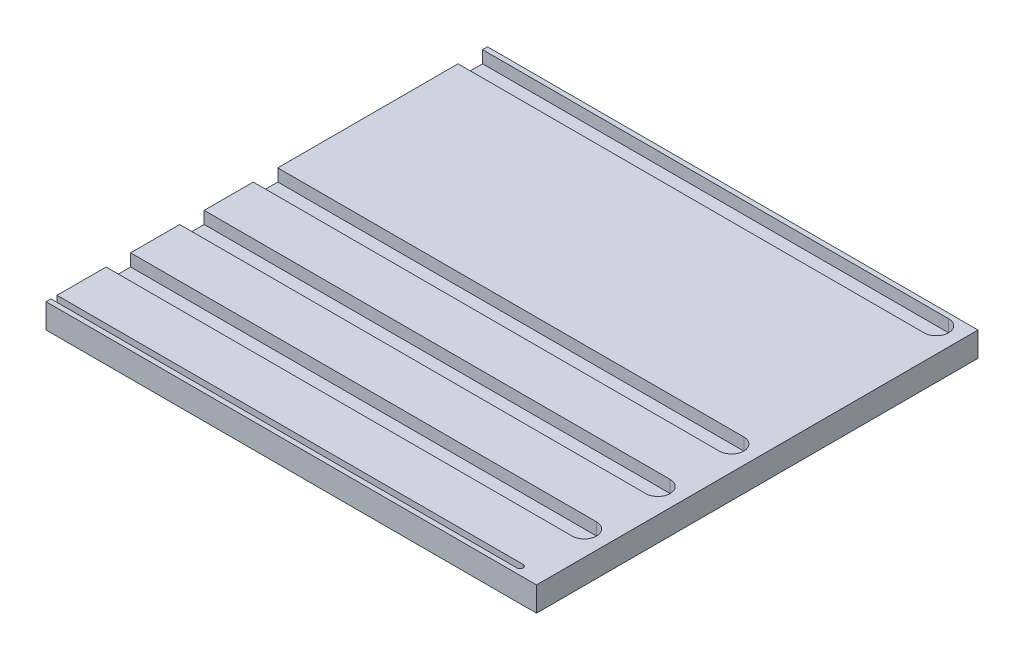
SolidWorks part; units mm, degrees
ref_plane "Front Plane" through (0, 0, 0) normal (0, 0, 1) x (1, 0, 0)
ref_plane "Top Plane" through (0, 0, 0) normal (0, 1, 0) x (1, 0, 0)
ref_plane "Right Plane" through (0, 0, 0) normal (1, 0, 0) x (0, 0, -1)
sketch "Sketch1" plane through (0, 0, 0) normal (0, 1, 0) x (1, 0, 0)
  line L1 (0, 0) -> (127, 0)
  line L2 (0, 0) -> (0, 114.3)
  line L3 (0, 114.3) -> (127, 114.3)
  line L4 (127, 0) -> (127, 114.3)
  dimension "D1" = 127
  dimension "D2" = 114.3
extrude "Boss-Extrude1" add sketch "Sketch1" against normal blind 6.35
sketch "Sketch2" plane through (0, 0, 0) normal (0, 1, 0) x (1, 0, 0)
  line L0 (0, 114.3) -> (0, 0) construction
  line L1 (0, 1.27) -> (120.65, 1.27)
  line L2 (0, 1.27) -> (0, 2.8575)
  line L3 (0, 2.8575) -> (120.65, 2.8575)
  line L4 (120.65, 1.27) -> (120.65, 2.8575)
  line L6 (0, 15.5575) -> (120.65, 15.5575)
  line L7 (0, 15.5575) -> (0, 21.9075)
  line L8 (0, 21.9075) -> (120.65, 21.9075)
  line L9 (120.65, 15.5575) -> (120.65, 21.9075)
  line L10 (0, 34.6075) -> (120.65, 34.6075)
  line L11 (0, 34.6075) -> (0, 40.9575)
  line L12 (0, 40.9575) -> (120.65, 40.9575)
  line L13 (120.65, 34.6075) -> (120.65, 40.9575)
  line L14 (0, 53.6575) -> (120.65, 53.6575)
  line L15 (0, 53.6575) -> (0, 60.0075)
  line L16 (0, 60.0075) -> (120.65, 60.0075)
  line L17 (120.65, 53.6575) -> (120.65, 60.0075)
  line L18 (0, 106.68) -> (120.65, 106.68)
  line L19 (0, 106.68) -> (0, 113.03)
  line L20 (0, 113.03) -> (120.65, 113.03)
  line L21 (120.65, 106.68) -> (120.65, 113.03)
  arc A0 (120.65, 34.6075) -> (120.65, 40.9575) centre (120.65, 37.7825) ccw
  arc A1 (120.65, 1.27) -> (120.65, 2.8575) centre (120.65, 2.0638) ccw
  arc A2 (120.65, 15.5575) -> (120.65, 21.9075) centre (120.65, 18.7325) ccw
  arc A3 (120.65, 53.6575) -> (120.65, 60.0075) centre (120.65, 56.8325) ccw
  arc A4 (120.65, 106.68) -> (120.65, 113.03) centre (120.65, 109.855) ccw
  line M1 (0, 114.3) -> (0, 0)
  dimension "D1" = 6.35
  dimension "D2" = 6.35
  dimension "D3" = 6.35
  dimension "D4" = 6.35
  dimension "D5" = 1.5875
  dimension "D6" = 1.27
  dimension "D7" = 12.7
  dimension "D8" = 12.7
  dimension "D9" = 12.7
  dimension "D10" = 1.27
  dimension "D11" = 6.35
  dimension "D12" = 6.35
  dimension "D13" = 6.35
  dimension "D14" = 6.35
  dimension "D15" = 6.35
extrude "Cut-Extrude1" cut sketch "Sketch2" against normal blind 3.175 contours L18 L21 L20 M1 | L21 A4 | L14 L17 L16 M1 | L10 L13 L12 M1 | L6 L9 L8 M1 | L1 L4 L3 M1 | L4 A1 | L9 A2 | L13 A0 | L17 A3
